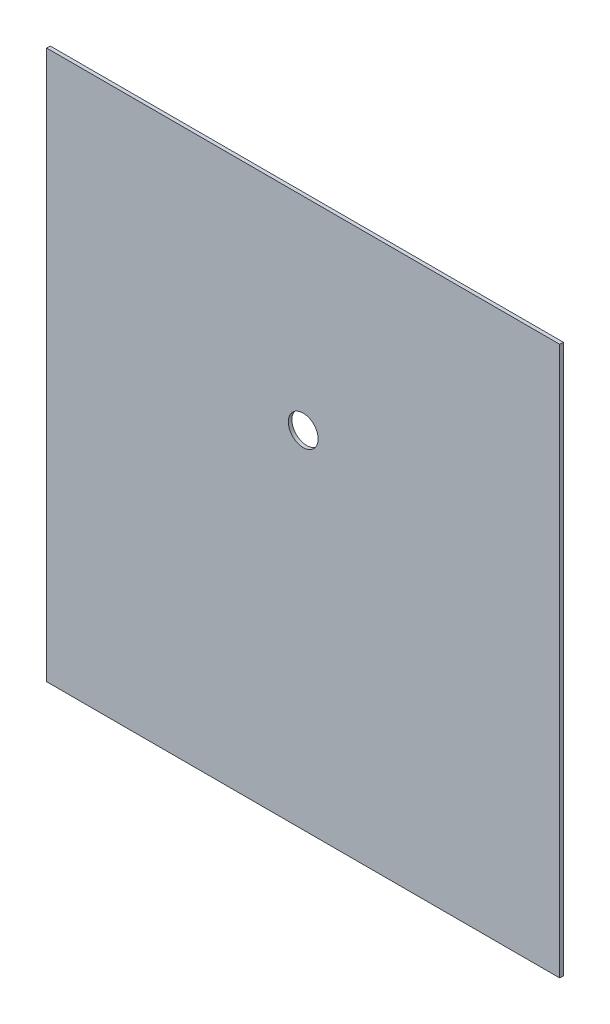
SolidWorks part; units mm, degrees
ref_plane "Front Plane" through (0, 0, 0) normal (0, 0, 1) x (1, 0, 0)
ref_plane "Top Plane" through (0, 0, 0) normal (0, 1, 0) x (1, 0, 0)
ref_plane "Right Plane" through (0, 0, 0) normal (1, 0, 0) x (0, 0, -1)
sketch "Sketch1" plane through (0, 0, 0) normal (0, 0, 1) x (1, 0, 0)
  line L0 (0, 427.6735) -> (0, 0) construction
  line L1 (0, 0) -> (427.6735, 0) construction
  line L3 (-215, 230) -> (215, 230)
  line L4 (-215, 230) -> (-215, -230)
  line L5 (-215, -230) -> (215, -230)
  line L6 (215, 230) -> (215, -230)
  circle A1 centre (0, 60) radius 12.5
  dimension "D3" = 60
  dimension "D4" = 25
  dimension "D1" = 460
  dimension "D2" = 430
extrude "Boss-Extrude1" add sketch "Sketch1" along normal blind 3
